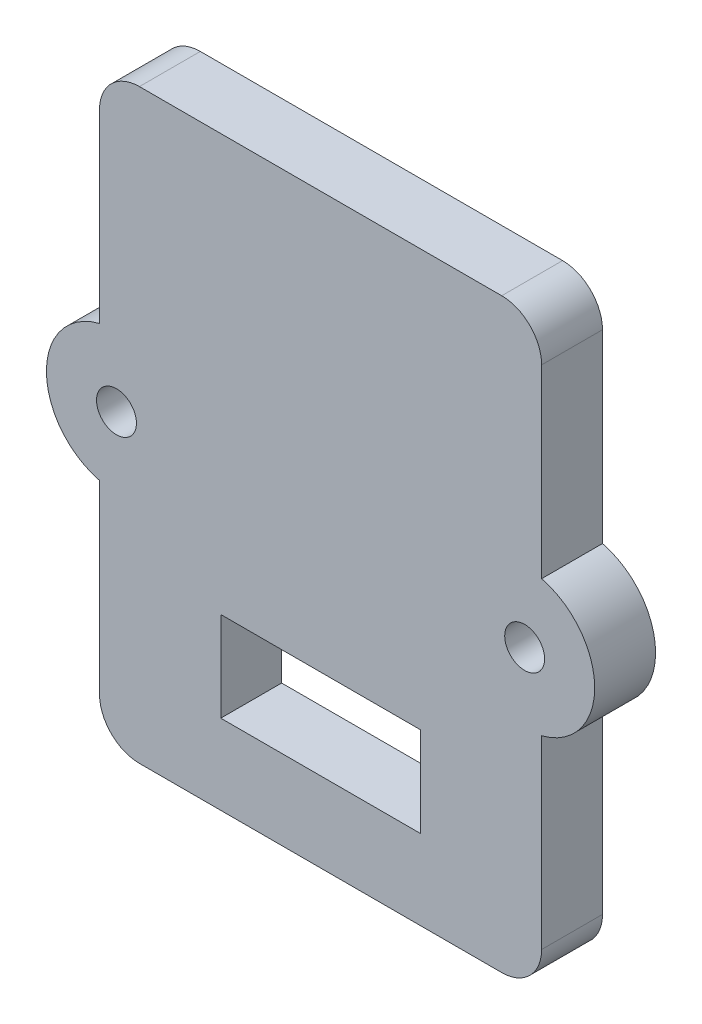
SolidWorks part; units mm, degrees
ref_plane "Front Plane" through (0, 0, 0) normal (0, 0, 1) x (1, 0, 0)
ref_plane "Top Plane" through (0, 0, 0) normal (0, 1, 0) x (1, 0, 0)
ref_plane "Right Plane" through (0, 0, 0) normal (1, 0, 0) x (0, 0, -1)
sketch "Sketch2" plane through (0, 0, 0) normal (0, 0, 1) x (1, 0, 0)
  line L0 (0, -2.537) -> (0, 27.1336) construction
  line L1 (-0.1673, 27.1336) -> (0.1673, 27.1336) construction
  line L2 (-13.9298, 12.45) -> (13.735, 12.45) construction
  line L3 (-11.075, 15.8555) -> (-11.075, 25.1336)
  line L4 (-9.075, -2.2336) -> (9.075, -2.2336)
  line L5 (-11.075, -0.2336) -> (-11.075, 9.0445)
  line L6 (-9.075, 27.1336) -> (9.075, 27.1336)
  line L7 (11.075, -0.2336) -> (11.075, 9.0445)
  line L8 (0, 27.1336) -> (0, -2.2336) construction
  line L9 (-11.075, 12.45) -> (11.075, 12.45) construction
  line L10 (11.075, 15.8555) -> (11.075, 25.1336)
  line L12 (-5, 1.7664) -> (5, 1.7664)
  line L13 (-5, 1.7664) -> (-5, 6.2664)
  line L14 (-5, 6.2664) -> (5, 6.2664)
  line L15 (5, 1.7664) -> (5, 6.2664)
  line L16 (0, 6.2664) -> (0, 1.7664) construction
  line L17 (-5, 4.0164) -> (5, 4.0164) construction
  arc A0 (11.06, 9.0408) -> (11.06, 15.8592) centre (10.225, 12.45) ccw construction
  circle A1 centre (-10.225, 12.45) radius 1
  circle A2 centre (10.225, 12.45) radius 1
  arc A3 (-11.075, 15.8555) -> (-11.075, 9.0445) centre (-10.225, 12.45) ccw
  arc A4 (11.075, 15.8555) -> (11.075, 9.0445) centre (10.225, 12.45) cw
  arc A5 (-9.075, -2.2336) -> (-11.075, -0.2336) centre (-9.075, -0.2336) cw
  arc A6 (9.075, -2.2336) -> (11.075, -0.2336) centre (9.075, -0.2336) ccw
  arc A7 (9.075, 27.1336) -> (11.075, 25.1336) centre (9.075, 25.1336) cw
  arc A8 (-11.075, 25.1336) -> (-9.075, 27.1336) centre (-9.075, 25.1336) cw
  point P14 (0, 12.45)
  point P31 (0, 4.0164)
  dimension "D3" = 2
  dimension "D1" = 22.15
  dimension "D2" = 29.3672
  dimension "D4" = 10
  dimension "D5" = 4.5
  dimension "D6" = 4
extrude "Boss-Extrude2" add sketch "Sketch2" along normal blind 3.05
